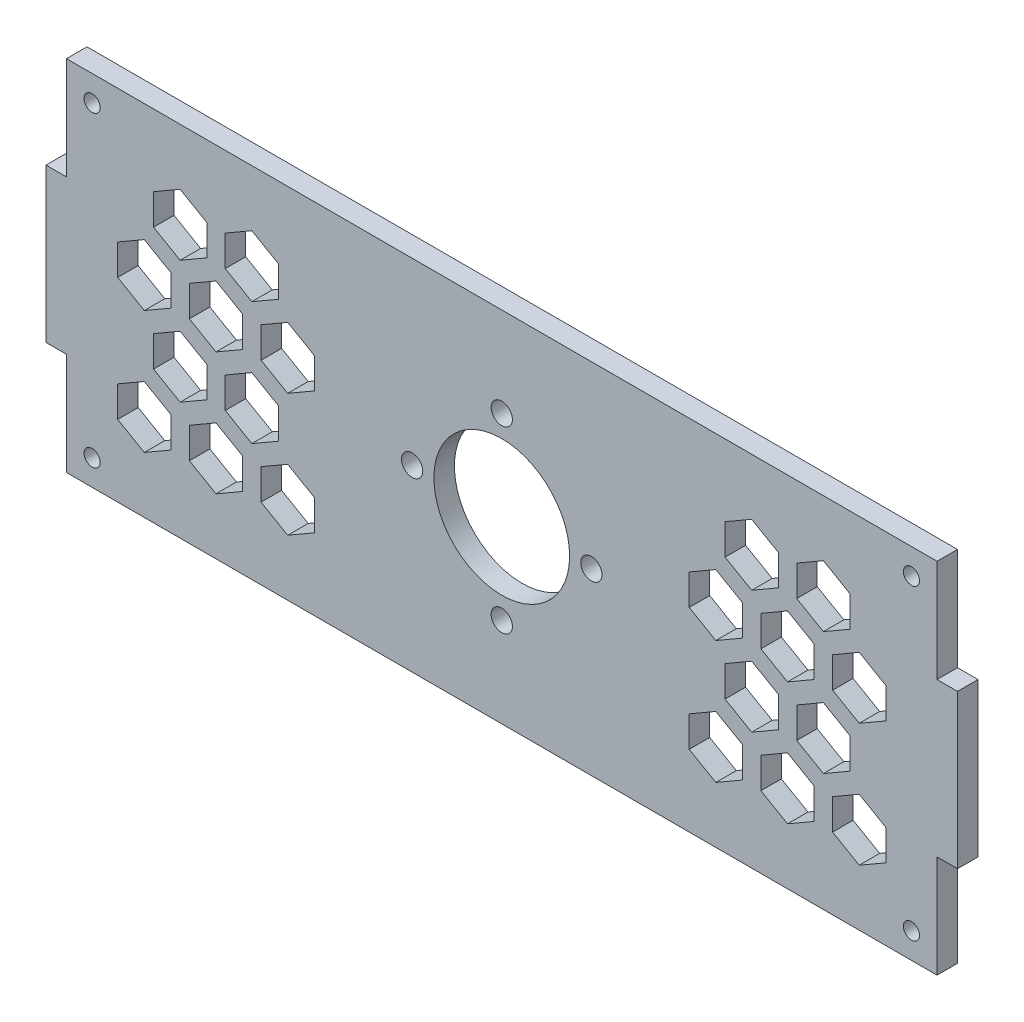
SolidWorks part; units mm, degrees
ref_plane "前视基准面" through (0, 0, 0) normal (0, 0, 1) x (1, 0, 0)
ref_plane "上视基准面" through (0, 0, 0) normal (0, 1, 0) x (1, 0, 0)
ref_plane "右视基准面" through (0, 0, 0) normal (1, 0, 0) x (0, 0, -1)
other "Configuration Table"
sketch "草图1" plane through (0, 0, 0) normal (0, 0, 1) x (1, 0, 0)
  line L1 (0, 0) -> (178, 0)
  line L2 (0, 0) -> (0, -70)
  line L3 (0, -70) -> (178, -70)
  line L4 (178, 0) -> (178, -70)
  dimension "D1" = 178
  dimension "D2" = 70
extrude "凸台-拉伸1" add sketch "草图1" along normal blind 4
sketch "草图2" plane through (0, 0, 4) normal (0, 0, 1) x (1, 0, 0)
  line L0 (89, -35) -> (89, 0) construction
  line L1 (178, 0) -> (0, 0) construction
  line L2 (0, -35) -> (89, -35) construction
  line L3 (0, 0) -> (0, -70) construction
  line L4 (40.1962, -11) -> (35, -14)
  line L5 (4, 0) -> (4, -20)
  line L6 (178, 0) -> (174, 0)
  line L7 (178, 0) -> (178, -20)
  line L8 (178, -20) -> (174, -20)
  line L9 (174, 0) -> (174, -20)
  line L10 (0, -20) -> (4, -20)
  line L11 (0, 0) -> (0, -20)
  line L12 (0, 0) -> (4, 0)
  line L13 (174, -70) -> (174, -50)
  line L14 (178, -50) -> (174, -50)
  line L15 (178, -70) -> (178, -50)
  line L16 (178, -70) -> (174, -70)
  line L17 (0, -70) -> (4, -70)
  line L18 (0, -70) -> (0, -50)
  line L19 (0, -50) -> (4, -50)
  line L20 (4, -70) -> (4, -50)
  line L21 (26.1962, -23) -> (31.3923, -20)
  line L22 (31.3923, -20) -> (31.3923, -14)
  line L23 (31.3923, -14) -> (26.1962, -11)
  line L24 (26.1962, -11) -> (21, -14)
  line L25 (21, -14) -> (21, -20)
  line L26 (21, -20) -> (26.1962, -23)
  line L27 (45.3923, -14) -> (40.1962, -11)
  line L28 (45.3923, -20) -> (45.3923, -14)
  line L29 (40.1962, -23) -> (45.3923, -20)
  line L30 (35, -20) -> (40.1962, -23)
  line L31 (35, -14) -> (35, -20)
  line L32 (33.1962, -23) -> (33.1962, -35) construction
  line L33 (33.1962, -35) -> (38.3923, -32)
  line L34 (38.3923, -32) -> (38.3923, -26)
  line L35 (38.3923, -26) -> (33.1962, -23)
  line L36 (33.1962, -23) -> (28, -26)
  line L37 (28, -26) -> (28, -32)
  line L38 (28, -32) -> (33.1962, -35)
  line L39 (47.1962, -23) -> (42, -26)
  line L40 (52.3923, -26) -> (47.1962, -23)
  line L41 (52.3923, -32) -> (52.3923, -26)
  line L42 (42, -32) -> (47.1962, -35)
  line L43 (47.1962, -35) -> (52.3923, -32)
  line L44 (42, -26) -> (42, -32)
  line L45 (14, -26) -> (19.1962, -23)
  line L46 (19.1962, -23) -> (24.3923, -26)
  line L47 (24.3923, -26) -> (24.3923, -32)
  line L48 (19.1962, -35) -> (14, -32)
  line L49 (24.3923, -32) -> (19.1962, -35)
  line L50 (14, -32) -> (14, -26)
  line L51 (14, -29) -> (52.3923, -29) construction
  line L52 (35, -44) -> (35, -38)
  line L53 (35, -38) -> (40.1962, -35)
  line L54 (40.1962, -35) -> (45.3923, -38)
  line L55 (45.3923, -38) -> (45.3923, -44)
  line L56 (45.3923, -44) -> (40.1962, -47)
  line L57 (21, -38) -> (26.1962, -35)
  line L58 (21, -44) -> (21, -38)
  line L59 (26.1962, -47) -> (21, -44)
  line L60 (31.3923, -44) -> (26.1962, -47)
  line L61 (31.3923, -38) -> (31.3923, -44)
  line L62 (26.1962, -35) -> (31.3923, -38)
  line L63 (40.1962, -47) -> (35, -44)
  line L64 (21, -41) -> (45.3923, -41) construction
  line L65 (14, -53) -> (52.3923, -53) construction
  line L66 (33.1962, -59) -> (33.1962, -47) construction
  line L67 (14, -50) -> (14, -56)
  line L68 (24.3923, -50) -> (19.1962, -47)
  line L69 (19.1962, -47) -> (14, -50)
  line L70 (24.3923, -56) -> (24.3923, -50)
  line L71 (19.1962, -59) -> (24.3923, -56)
  line L72 (14, -56) -> (19.1962, -59)
  line L73 (42, -56) -> (42, -50)
  line L74 (47.1962, -47) -> (52.3923, -50)
  line L75 (42, -50) -> (47.1962, -47)
  line L76 (52.3923, -50) -> (52.3923, -56)
  line L77 (52.3923, -56) -> (47.1962, -59)
  line L78 (47.1962, -59) -> (42, -56)
  line L79 (28, -50) -> (33.1962, -47)
  line L80 (28, -56) -> (28, -50)
  line L81 (33.1962, -59) -> (28, -56)
  line L82 (38.3923, -56) -> (33.1962, -59)
  line L83 (38.3923, -50) -> (38.3923, -56)
  line L84 (33.1962, -47) -> (38.3923, -50)
  line L85 (144.8038, -59) -> (144.8038, -47) construction
  line L86 (164, -53) -> (125.6077, -53) construction
  line L87 (157, -41) -> (132.6077, -41) construction
  line L88 (164, -29) -> (125.6077, -29) construction
  line L89 (144.8038, -23) -> (144.8038, -35) construction
  line L90 (144.8038, -47) -> (139.6077, -50)
  line L91 (139.6077, -50) -> (139.6077, -56)
  line L92 (139.6077, -56) -> (144.8038, -59)
  line L93 (144.8038, -59) -> (150, -56)
  line L94 (150, -56) -> (150, -50)
  line L95 (150, -50) -> (144.8038, -47)
  line L96 (130.8038, -59) -> (136, -56)
  line L97 (125.6077, -56) -> (130.8038, -59)
  line L98 (125.6077, -50) -> (125.6077, -56)
  line L99 (136, -50) -> (130.8038, -47)
  line L100 (130.8038, -47) -> (125.6077, -50)
  line L101 (136, -56) -> (136, -50)
  line L102 (164, -56) -> (158.8038, -59)
  line L103 (158.8038, -59) -> (153.6077, -56)
  line L104 (153.6077, -56) -> (153.6077, -50)
  line L105 (158.8038, -47) -> (164, -50)
  line L106 (153.6077, -50) -> (158.8038, -47)
  line L107 (164, -50) -> (164, -56)
  line L108 (137.8038, -47) -> (143, -44)
  line L109 (151.8038, -35) -> (146.6077, -38)
  line L110 (146.6077, -38) -> (146.6077, -44)
  line L111 (146.6077, -44) -> (151.8038, -47)
  line L112 (151.8038, -47) -> (157, -44)
  line L113 (157, -44) -> (157, -38)
  line L114 (157, -38) -> (151.8038, -35)
  line L115 (132.6077, -44) -> (137.8038, -47)
  line L116 (132.6077, -38) -> (132.6077, -44)
  line L117 (137.8038, -35) -> (132.6077, -38)
  line L118 (143, -38) -> (137.8038, -35)
  line L119 (143, -44) -> (143, -38)
  line L120 (164, -32) -> (164, -26)
  line L121 (153.6077, -32) -> (158.8038, -35)
  line L122 (158.8038, -35) -> (164, -32)
  line L123 (153.6077, -26) -> (153.6077, -32)
  line L124 (158.8038, -23) -> (153.6077, -26)
  line L125 (164, -26) -> (158.8038, -23)
  line L126 (136, -26) -> (136, -32)
  line L127 (130.8038, -35) -> (125.6077, -32)
  line L128 (136, -32) -> (130.8038, -35)
  line L129 (125.6077, -32) -> (125.6077, -26)
  line L130 (125.6077, -26) -> (130.8038, -23)
  line L131 (130.8038, -23) -> (136, -26)
  line L132 (150, -32) -> (144.8038, -35)
  line L133 (150, -26) -> (150, -32)
  line L134 (144.8038, -23) -> (150, -26)
  line L135 (139.6077, -26) -> (144.8038, -23)
  line L136 (139.6077, -32) -> (139.6077, -26)
  line L137 (144.8038, -35) -> (139.6077, -32)
  line L138 (143, -14) -> (143, -20)
  line L139 (143, -20) -> (137.8038, -23)
  line L140 (137.8038, -23) -> (132.6077, -20)
  line L141 (132.6077, -20) -> (132.6077, -14)
  line L142 (132.6077, -14) -> (137.8038, -11)
  line L143 (157, -20) -> (151.8038, -23)
  line L144 (157, -14) -> (157, -20)
  line L145 (151.8038, -11) -> (157, -14)
  line L146 (146.6077, -14) -> (151.8038, -11)
  line L147 (146.6077, -20) -> (146.6077, -14)
  line L148 (151.8038, -23) -> (146.6077, -20)
  line L149 (137.8038, -11) -> (143, -14)
  circle A0 centre (89, -35) radius 13.25
  circle A1 centre (89, -17.5) radius 2.075
  circle A2 centre (106.5, -35) radius 2.075
  circle A3 centre (89, -52.5) radius 2.075
  circle A4 centre (71.5, -35) radius 2.075
  circle A17 centre (9, -5) radius 1.575
  circle A18 centre (9, -65) radius 1.575
  circle A19 centre (169, -65) radius 1.575
  circle A20 centre (169, -5) radius 1.575
  circle A21 centre (26.1962, -17) radius 5.1962 construction
  circle A22 centre (33.1962, -29) radius 5.1962 construction
  circle A23 centre (26.1962, -41) radius 5.1962 construction
  circle A24 centre (33.1962, -53) radius 5.1962 construction
  circle A25 centre (144.8038, -53) radius 5.1962 construction
  circle A26 centre (151.8038, -41) radius 5.1962 construction
  circle A27 centre (144.8038, -29) radius 5.1962 construction
  circle A28 centre (151.8038, -17) radius 5.1962 construction
  point P19 (89, -35)
  dimension "D1" = 26.5
  dimension "D3" = 4.15
  dimension "D5" = 6
  dimension "D8" = 2
  dimension "D11" = 3.15
  dimension "D2" = 17.5
  dimension "D6" = 11
  dimension "D7" = 17
  dimension "D9" = 4
  dimension "D10" = 20
  dimension "D12" = 5
  dimension "D13" = 5
  dimension "D14" = 3.6077
  dimension "D15" = 6
  dimension "D16" = 3
  dimension "D18" = 3.6077
  dimension "D17" = 2
  dimension "D4" = 4
extrude "切除-拉伸1" cut sketch "草图2" against normal through all
